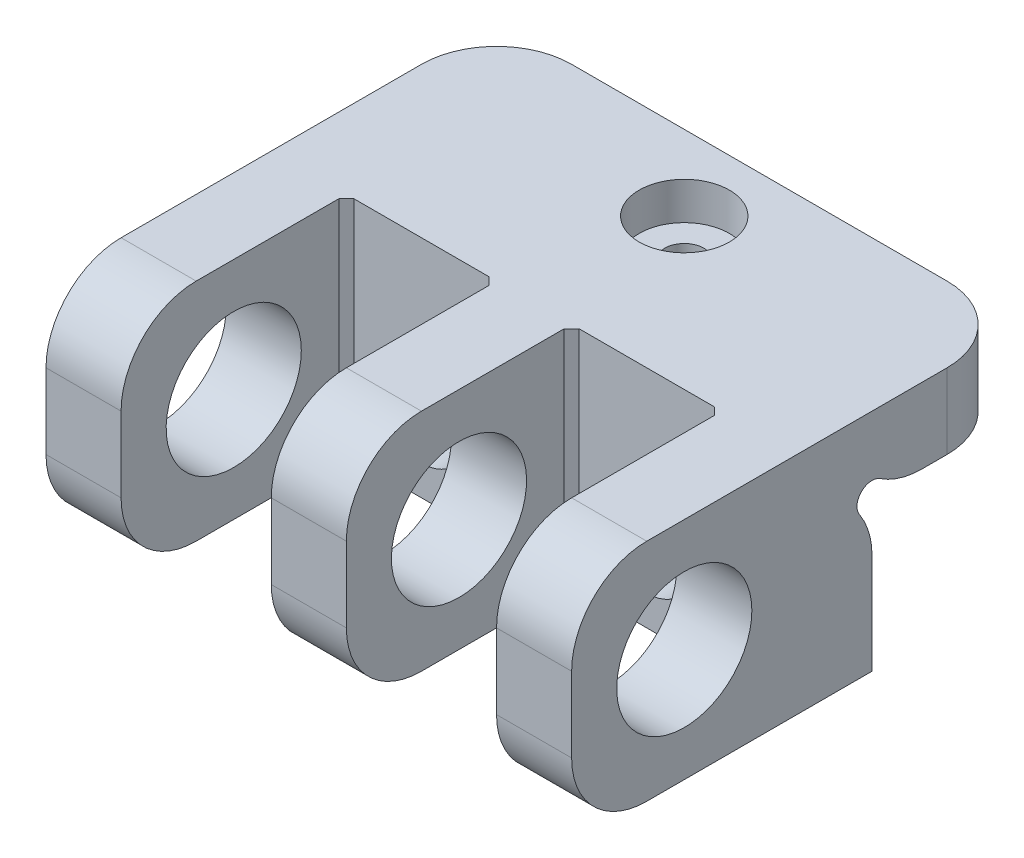
SolidWorks part; units mm, degrees
ref_plane "Płaszczyzna przednia" through (0, 0, 0) normal (0, 0, 1) x (1, 0, 0)
ref_plane "Płaszczyzna górna" through (0, 0, 0) normal (0, 1, 0) x (1, 0, 0)
ref_plane "Płaszczyzna prawa" through (0, 0, 0) normal (1, 0, 0) x (0, 0, -1)
sketch "Szkic1" plane through (0, 0, 0) normal (0, 0, 1) x (1, 0, 0)
  line L1 (-35, -15) -> (35, -15)
  line L2 (-35, -15) -> (-35, 15)
  line L3 (-35, 15) -> (35, 15)
  line L4 (35, -15) -> (35, 15)
  line L5 (-35, -15) -> (35, 15) construction
  line L6 (-35, 15) -> (35, -15) construction
  point P0 (0, 0)
  dimension "D1" = 70
  dimension "D2" = 30
extrude "Dodanie-wyciągnięcie1" add sketch "Szkic1" along normal blind 10
sketch "Szkic2" plane through (0, 0, 0) normal (0, 0, -1) x (-1, 0, 0)
  line L0 (35, 15) -> (35, -15) construction
  line L1 (-35, 15) -> (35, 15)
  line L2 (-35, 15) -> (-35, 5)
  line L3 (-35, 5) -> (35, 5)
  line L4 (35, 15) -> (35, 5)
  dimension "D1" = 10
extrude "Dodanie-wyciągnięcie2" add sketch "Szkic2" along normal blind 20
sketch "Szkic3" plane through (35, 0, 0) normal (1, 0, 0) x (0, 0, -1)
  circle A0 centre (0, 5) radius 2
  dimension "D1" = 4
extrude "Wytnij-wyciągnięcie1" cut sketch "Szkic3" against normal through all
fillet "Zaokrąglenie1" radius 10 2 edges at (0, 5, -2) (0, 3, 0)
sketch "Szkic4" plane through (0, 0, 10) normal (0, 0, 1) x (1, 0, 0)
  line L0 (-35, -15) -> (35, -15) construction
  line L1 (-35, 15) -> (-25, 15)
  line L2 (-35, 15) -> (-35, -15)
  line L3 (-35, -15) -> (-25, -15)
  line L4 (-25, 15) -> (-25, -15)
  line L5 (35, 15) -> (-35, 15) construction
  line L6 (-5, 15) -> (5, 15)
  line L7 (-5, 15) -> (-5, -15)
  line L8 (-5, -15) -> (5, -15)
  line L9 (5, 15) -> (5, -15)
  line L11 (35, 15) -> (25, 15)
  line L12 (35, 15) -> (35, -15)
  line L13 (35, -15) -> (25, -15)
  line L14 (25, 15) -> (25, -15)
  dimension "D1" = 10
  dimension "D2" = 10
  dimension "D3" = 20
  dimension "D4" = 10
extrude "Dodanie-wyciągnięcie3" add sketch "Szkic4" along normal blind 30
sketch "Szkic5" plane through (0, 0, 10) normal (0, 0, 1) x (1, 0, 0)
  line L0 (-25, -15) -> (-5, -15) construction
  line L2 (-5, 15) -> (-5, -15) construction
  circle A0 centre (-15, -5) radius 2.6
  point P6 (-7.1637, -5.7566)
  dimension "D3" = 5.2
  dimension "D1" = 10
  dimension "D2" = 10
extrude "Wytnij-wyciągnięcie2" cut sketch "Szkic5" against normal through all
sketch "Szkic6" plane through (0, 0, 10) normal (0, 0, 1) x (1, 0, 0)
  circle A0 centre (-15, -5) radius 6
  dimension "D1" = 12
extrude "Wytnij-wyciągnięcie3" cut sketch "Szkic6" against normal blind 5
ref_plane "Płaszczyzna1" through (0, 0, 0) normal (-1, 0, 0) x (0, 0, 1)
mirror "Lustro1" about plane through (0, 0, 0) normal (-1, 0, 0) of "Wytnij-wyciągnięcie2", "Wytnij-wyciągnięcie3"
sketch "Szkic7" plane through (0, 15, 0) normal (0, 1, 0) x (1, 0, 0)
  line L0 (-35, 20) -> (35, 20) construction
  line L1 (35, -40) -> (35, 20) construction
  circle A0 centre (0, 10) radius 2.6
  dimension "D1" = 5.2
  dimension "D2" = 10
  dimension "D3" = 35
extrude "Wytnij-wyciągnięcie4" cut sketch "Szkic7" against normal through all
sketch "Szkic8" plane through (0, 15, 0) normal (0, 1, 0) x (1, 0, 0)
  circle A0 centre (0, 10) radius 6
  dimension "D1" = 12
extrude "Wytnij-wyciągnięcie5" cut sketch "Szkic8" against normal blind 5
fillet "Zaokrąglenie2" radius 10 8 edges at (-30, -15, 40) (0, -15, 40) (30, -15, 40) (30, 15, 40) (0, 15, 40) (-30, 15, 40) (-35, 10, -20) (35, 10, -20)
sketch "Szkic9" plane through (35, 0, 0) normal (1, 0, 0) x (0, 0, -1)
  line L0 (-40, -5) -> (-40, 5) construction
  line L1 (-30, 15) -> (10, 15) construction
  circle A0 centre (-25, 0) radius 9
  dimension "D1" = 18
  dimension "D2" = 15
  dimension "D3" = 15
extrude "Wytnij-wyciągnięcie6" cut sketch "Szkic9" against normal through all
chamfer "Sfazowanie1" distance 1 angle 45 4 edges at (-25, 0, 10) (-5, 0, 10) (25, 0, 10) (5, 0, 10)
